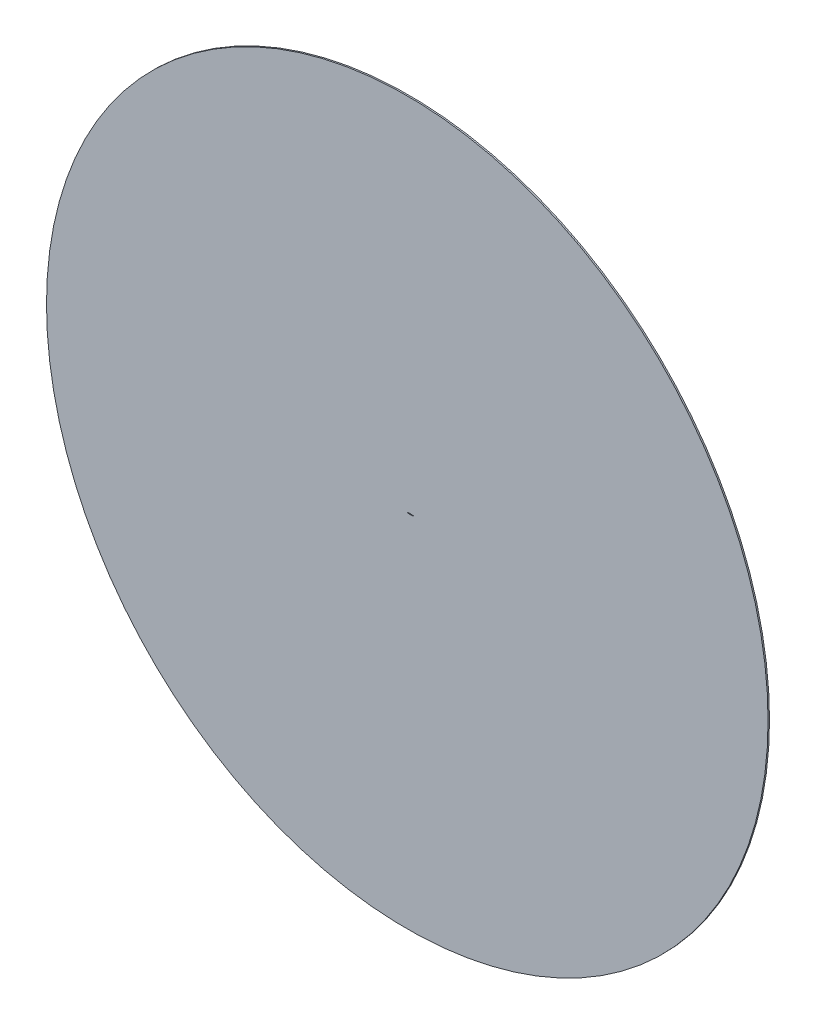
SolidWorks part; units mm, degrees
ref_plane "Front Plane" through (0, 0, 0) normal (0, 0, 1) x (1, 0, 0)
ref_plane "Top Plane" through (0, 0, 0) normal (0, 1, 0) x (1, 0, 0)
ref_plane "Right Plane" through (0, 0, 0) normal (1, 0, 0) x (0, 0, -1)
curve "Curve1"
  spline degree 3 poles (609.0266, -0.065, 0) (609.7435, 0, 0) (609.0266, 0.065, 0) (608.4348, 0.1812, 0) (606.982, 0.3745, 0) (605.1708, 0.6429, 0) (602.7599, 0.9868, 0) (599.8538, 1.4027, 0) (596.4201, 1.8894, 0) (592.4782, 2.4453, 0) (588.0305, 3.0658, 0) (583.0864, 3.7497, 0) (577.6538, 4.4919, 0) (571.7427, 5.2915, 0) (565.3633, 6.1431, 0) (558.5267, 7.0435, 0) (551.2452, 7.989, 0) (543.5311, 8.9751, 0) (535.3983, 9.9995, 0) (526.861, 11.0564, 0) (517.9338, 12.1418, 0) (508.6331, 13.2534, 0) (498.9745, 14.3843, 0) (488.9755, 15.5329, 0) (478.6533, 16.6942, 0) (468.0259, 17.8633, 0) (457.1122, 19.0358, 0) (445.9317, 20.2096, 0) (434.5033, 21.3779, 0) (422.8474, 22.5382, 0) (410.9843, 23.685, 0) (398.9349, 24.8131, 0) (386.7204, 25.9202, 0) (374.3624, 26.9991, 0) (361.8823, 28.0468, 0) (349.3021, 29.058, 0) (336.6435, 30.027, 0) (323.9291, 30.9493, 0) (311.1813, 31.8197, 0) (298.4224, 32.6341, 0) (285.6746, 33.3849, 0) (272.9601, 34.0701, 0) (260.3015, 34.6833, 0) (247.721, 35.219, 0) (235.2407, 35.6733, 0) (222.8825, 36.0416, 0) (210.6677, 36.3202, 0) (198.618, 36.5039, 0) (186.7544, 36.5908, 0) (175.098, 36.576, 0) (163.669, 36.4591, 0) (152.4878, 36.2354, 0) (141.5734, 35.9063, 0) (130.9453, 35.4671, 0) (120.622, 34.9205, 0) (110.622, 34.2646, 0) (100.9624, 33.5002, 0) (91.6602, 32.63, 0) (82.7316, 31.6541, 0) (74.1925, 30.5757, 0) (66.0576, 29.3979, 0) (58.3413, 28.1224, 0) (51.0569, 26.7548, 0) (44.2171, 25.2975, 0) (37.8335, 23.7562, 0) (31.9176, 22.1329, 0) (26.4786, 20.4359, 0) (21.5267, 18.6662, 0) (17.0689, 16.8301, 0) (13.1127, 14.9307, 0) (9.6631, 12.973, 0) (6.7256, 10.9577, 0) (4.3029, 8.8862, 0) (2.3998, 6.7558, 0) (1.0219, 4.5626, 0) (0.1859, 2.3028, 0) (-0.0912, 0, 0) (0.1859, -2.3028, 0) (1.0219, -4.5626, 0) (2.3998, -6.7558, 0) (4.3029, -8.8862, 0) (6.7256, -10.9577, 0) (9.6631, -12.973, 0) (13.1127, -14.9307, 0) (17.0689, -16.8301, 0) (21.5267, -18.6662, 0) (26.4786, -20.4359, 0) (31.9176, -22.1329, 0) (37.8335, -23.7562, 0) (44.2171, -25.2975, 0) (51.0569, -26.7548, 0) (58.3413, -28.1224, 0) (66.0576, -29.3979, 0) (74.1925, -30.5757, 0) (82.7316, -31.6541, 0) (91.6602, -32.63, 0) (100.9624, -33.5002, 0) (110.622, -34.2646, 0) (120.622, -34.9205, 0) (130.9453, -35.4671, 0) (141.5734, -35.9063, 0) (152.4878, -36.2354, 0) (163.669, -36.4591, 0) (175.098, -36.576, 0) (186.7544, -36.5908, 0) (198.618, -36.5039, 0) (210.6677, -36.3202, 0) (222.8825, -36.0416, 0) (235.2407, -35.6733, 0) (247.721, -35.219, 0) (260.3015, -34.6833, 0) (272.9601, -34.0701, 0) (285.6746, -33.3849, 0) (298.4224, -32.6341, 0) (311.1813, -31.8197, 0) (323.9291, -30.9493, 0) (336.6435, -30.027, 0) (349.3021, -29.058, 0) (361.8823, -28.0468, 0) (374.3624, -26.9991, 0) (386.7204, -25.9202, 0) (398.9349, -24.8131, 0) (410.9843, -23.685, 0) (422.8474, -22.5382, 0) (434.5033, -21.3779, 0) (445.9317, -20.2096, 0) (457.1122, -19.0358, 0) (468.0259, -17.8633, 0) (478.6533, -16.6942, 0) (488.9755, -15.5329, 0) (498.9745, -14.3843, 0) (508.6331, -13.2534, 0) (517.9338, -12.1418, 0) (526.861, -11.0564, 0) (535.3983, -9.9995, 0) (543.5311, -8.9751, 0) (551.2452, -7.989, 0) (558.5267, -7.0435, 0) (565.3633, -6.1431, 0) (571.7427, -5.2915, 0) (577.6538, -4.4919, 0) (583.0864, -3.7497, 0) (588.0305, -3.0658, 0) (592.4782, -2.4453, 0) (596.4201, -1.8894, 0) (599.8538, -1.4027, 0) (602.7599, -0.9868, 0) (605.1708, -0.6429, 0) (606.982, -0.3745, 0) (608.4348, -0.1812, 0) (609.0266, -0.065, 0) (609.7435, 0, 0) (609.0266, 0.065, 0) knots -0.001954 -0.000869 -0.000218 0 0.000218 0.000869 0.001954 0.003469 0.005413 0.007781 0.01057 0.013775 0.017389 0.021406 0.025819 0.03062 0.0358 0.041349 0.047259 0.053518 0.060115 0.067039 0.074276 0.081815 0.089641 0.097741 0.106101 0.114706 0.12354 0.132588 0.141833 0.15126 0.160852 0.170592 0.180463 0.190447 0.200526 0.210683 0.220901 0.23116 0.241444 0.251733 0.26201 0.272258 0.282457 0.292591 0.302642 0.312592 0.322425 0.332124 0.341671 0.351052 0.36025 0.369251 0.378038 0.386598 0.394918 0.402982 0.41078 0.418299 0.425526 0.432452 0.439066 0.445359 0.451323 0.456949 0.462232 0.467167 0.471749 0.475977 0.479852 0.483377 0.48656 0.489414 0.491961 0.494234 0.496281 0.498175 0.5 0.501825 0.503719 0.505766 0.508039 0.510586 0.51344 0.516623 0.520148 0.524023 0.528251 0.532833 0.537768 0.543051 0.548677 0.554641 0.560934 0.567548 0.574474 0.581701 0.58922 0.597018 0.605082 0.613402 0.621962 0.630749 0.63975 0.648948 0.658329 0.667876 0.677575 0.687408 0.697358 0.707409 0.717543 0.727742 0.73799 0.748267 0.758556 0.76884 0.779099 0.789317 0.799474 0.809553 0.819537 0.829408 0.839148 0.84874 0.858167 0.867412 0.87646 0.885294 0.893899 0.902259 0.910359 0.918185 0.925724 0.932961 0.939885 0.946482 0.952741 0.958651 0.9642 0.96938 0.974181 0.978594 0.982611 0.986225 0.98943 0.992219 0.994587 0.996531 0.998046 0.999131 0.999782 1 1.000218 1.000869 1.001954 periodic
sketch "Sketch1" plane through (0, 0, 0) normal (0, 0, 1) x (1, 0, 0)
  circle A0 centre (0, 0) radius 30480
  spline S0 degree 3 poles (609.0266, -0.065) (609.7435, 0) (609.0266, 0.065) (608.4348, 0.1812) (606.982, 0.3745) (605.1708, 0.6429) (602.7599, 0.9868) (599.8538, 1.4027) (596.4201, 1.8894) (592.4782, 2.4453) (588.0305, 3.0658) (583.0864, 3.7497) (577.6538, 4.4919) (571.7427, 5.2915) (565.3633, 6.1431) (558.5267, 7.0435) (551.2452, 7.989) (543.5311, 8.9751) (535.3983, 9.9995) (526.861, 11.0564) (517.9338, 12.1418) (508.6331, 13.2534) (498.9745, 14.3843) (488.9755, 15.5329) (478.6533, 16.6942) (468.0259, 17.8633) (457.1122, 19.0358) (445.9317, 20.2096) (434.5033, 21.3779) (422.8474, 22.5382) (410.9843, 23.685) (398.9349, 24.8131) (386.7204, 25.9202) (374.3624, 26.9991) (361.8823, 28.0468) (349.3021, 29.058) (336.6435, 30.027) (323.9291, 30.9493) (311.1813, 31.8197) (298.4224, 32.6341) (285.6746, 33.3849) (272.9601, 34.0701) (260.3015, 34.6833) (247.721, 35.219) (235.2407, 35.6733) (222.8825, 36.0416) (210.6677, 36.3202) (198.618, 36.5039) (186.7544, 36.5908) (175.098, 36.576) (163.669, 36.4591) (152.4878, 36.2354) (141.5734, 35.9063) (130.9453, 35.4671) (120.622, 34.9205) (110.622, 34.2646) (100.9624, 33.5002) (91.6602, 32.63) (82.7316, 31.6541) (74.1925, 30.5757) (66.0576, 29.3979) (58.3413, 28.1224) (51.0569, 26.7548) (44.2171, 25.2975) (37.8335, 23.7562) (31.9176, 22.1329) (26.4786, 20.4359) (21.5267, 18.6662) (17.0689, 16.8301) (13.1127, 14.9307) (9.6631, 12.973) (6.7256, 10.9577) (4.3029, 8.8862) (2.3998, 6.7558) (1.0219, 4.5626) (0.1859, 2.3028) (-0.0912, 0) (0.1859, -2.3028) (1.0219, -4.5626) (2.3998, -6.7558) (4.3029, -8.8862) (6.7256, -10.9577) (9.6631, -12.973) (13.1127, -14.9307) (17.0689, -16.8301) (21.5267, -18.6662) (26.4786, -20.4359) (31.9176, -22.1329) (37.8335, -23.7562) (44.2171, -25.2975) (51.0569, -26.7548) (58.3413, -28.1224) (66.0576, -29.3979) (74.1925, -30.5757) (82.7316, -31.6541) (91.6602, -32.63) (100.9624, -33.5002) (110.622, -34.2646) (120.622, -34.9205) (130.9453, -35.4671) (141.5734, -35.9063) (152.4878, -36.2354) (163.669, -36.4591) (175.098, -36.576) (186.7544, -36.5908) (198.618, -36.5039) (210.6677, -36.3202) (222.8825, -36.0416) (235.2407, -35.6733) (247.721, -35.219) (260.3015, -34.6833) (272.9601, -34.0701) (285.6746, -33.3849) (298.4224, -32.6341) (311.1813, -31.8197) (323.9291, -30.9493) (336.6435, -30.027) (349.3021, -29.058) (361.8823, -28.0468) (374.3624, -26.9991) (386.7204, -25.9202) (398.9349, -24.8131) (410.9843, -23.685) (422.8474, -22.5382) (434.5033, -21.3779) (445.9317, -20.2096) (457.1122, -19.0358) (468.0259, -17.8633) (478.6533, -16.6942) (488.9755, -15.5329) (498.9745, -14.3843) (508.6331, -13.2534) (517.9338, -12.1418) (526.861, -11.0564) (535.3983, -9.9995) (543.5311, -8.9751) (551.2452, -7.989) (558.5267, -7.0435) (565.3633, -6.1431) (571.7427, -5.2915) (577.6538, -4.4919) (583.0864, -3.7497) (588.0305, -3.0658) (592.4782, -2.4453) (596.4201, -1.8894) (599.8538, -1.4027) (602.7599, -0.9868) (605.1708, -0.6429) (606.982, -0.3745) (608.4348, -0.1812) (609.0266, -0.065) (609.7435, 0) (609.0266, 0.065) knots -0.001954 -0.000869 -0.000218 0 0.000218 0.000869 0.001954 0.003469 0.005413 0.007781 0.01057 0.013775 0.017389 0.021406 0.025819 0.03062 0.0358 0.041349 0.047259 0.053518 0.060115 0.067039 0.074276 0.081815 0.089641 0.097741 0.106101 0.114706 0.12354 0.132588 0.141833 0.15126 0.160852 0.170592 0.180463 0.190447 0.200526 0.210683 0.220901 0.23116 0.241444 0.251733 0.26201 0.272258 0.282457 0.292591 0.302642 0.312592 0.322425 0.332124 0.341671 0.351052 0.36025 0.369251 0.378038 0.386598 0.394918 0.402982 0.41078 0.418299 0.425526 0.432452 0.439066 0.445359 0.451323 0.456949 0.462232 0.467167 0.471749 0.475977 0.479852 0.483377 0.48656 0.489414 0.491961 0.494234 0.496281 0.498175 0.5 0.501825 0.503719 0.505766 0.508039 0.510586 0.51344 0.516623 0.520148 0.524023 0.528251 0.532833 0.537768 0.543051 0.548677 0.554641 0.560934 0.567548 0.574474 0.581701 0.58922 0.597018 0.605082 0.613402 0.621962 0.630749 0.63975 0.648948 0.658329 0.667876 0.677575 0.687408 0.697358 0.707409 0.717543 0.727742 0.73799 0.748267 0.758556 0.76884 0.779099 0.789317 0.799474 0.809553 0.819537 0.829408 0.839148 0.84874 0.858167 0.867412 0.87646 0.885294 0.893899 0.902259 0.910359 0.918185 0.925724 0.932961 0.939885 0.946482 0.952741 0.958651 0.9642 0.96938 0.974181 0.978594 0.982611 0.986225 0.98943 0.992219 0.994587 0.996531 0.998046 0.999131 0.999782 1 1.000218 1.000869 1.001954 only from (609.6, 0) to (609.6, 0) construction
  spline S1 degree 3 poles (609.0266, -0.065) (609.7435, 0) (609.0266, 0.065) (608.4348, 0.1812) (606.982, 0.3745) (605.1708, 0.6429) (602.7599, 0.9868) (599.8538, 1.4027) (596.4201, 1.8894) (592.4782, 2.4453) (588.0305, 3.0658) (583.0864, 3.7497) (577.6538, 4.4919) (571.7427, 5.2915) (565.3633, 6.1431) (558.5267, 7.0435) (551.2452, 7.989) (543.5311, 8.9751) (535.3983, 9.9995) (526.861, 11.0564) (517.9338, 12.1418) (508.6331, 13.2534) (498.9745, 14.3843) (488.9755, 15.5329) (478.6533, 16.6942) (468.0259, 17.8633) (457.1122, 19.0358) (445.9317, 20.2096) (434.5033, 21.3779) (422.8474, 22.5382) (410.9843, 23.685) (398.9349, 24.8131) (386.7204, 25.9202) (374.3624, 26.9991) (361.8823, 28.0468) (349.3021, 29.058) (336.6435, 30.027) (323.9291, 30.9493) (311.1813, 31.8197) (298.4224, 32.6341) (285.6746, 33.3849) (272.9601, 34.0701) (260.3015, 34.6833) (247.721, 35.219) (235.2407, 35.6733) (222.8825, 36.0416) (210.6677, 36.3202) (198.618, 36.5039) (186.7544, 36.5908) (175.098, 36.576) (163.669, 36.4591) (152.4878, 36.2354) (141.5734, 35.9063) (130.9453, 35.4671) (120.622, 34.9205) (110.622, 34.2646) (100.9624, 33.5002) (91.6602, 32.63) (82.7316, 31.6541) (74.1925, 30.5757) (66.0576, 29.3979) (58.3413, 28.1224) (51.0569, 26.7548) (44.2171, 25.2975) (37.8335, 23.7562) (31.9176, 22.1329) (26.4786, 20.4359) (21.5267, 18.6662) (17.0689, 16.8301) (13.1127, 14.9307) (9.6631, 12.973) (6.7256, 10.9577) (4.3029, 8.8862) (2.3998, 6.7558) (1.0219, 4.5626) (0.1859, 2.3028) (-0.0912, 0) (0.1859, -2.3028) (1.0219, -4.5626) (2.3998, -6.7558) (4.3029, -8.8862) (6.7256, -10.9577) (9.6631, -12.973) (13.1127, -14.9307) (17.0689, -16.8301) (21.5267, -18.6662) (26.4786, -20.4359) (31.9176, -22.1329) (37.8335, -23.7562) (44.2171, -25.2975) (51.0569, -26.7548) (58.3413, -28.1224) (66.0576, -29.3979) (74.1925, -30.5757) (82.7316, -31.6541) (91.6602, -32.63) (100.9624, -33.5002) (110.622, -34.2646) (120.622, -34.9205) (130.9453, -35.4671) (141.5734, -35.9063) (152.4878, -36.2354) (163.669, -36.4591) (175.098, -36.576) (186.7544, -36.5908) (198.618, -36.5039) (210.6677, -36.3202) (222.8825, -36.0416) (235.2407, -35.6733) (247.721, -35.219) (260.3015, -34.6833) (272.9601, -34.0701) (285.6746, -33.3849) (298.4224, -32.6341) (311.1813, -31.8197) (323.9291, -30.9493) (336.6435, -30.027) (349.3021, -29.058) (361.8823, -28.0468) (374.3624, -26.9991) (386.7204, -25.9202) (398.9349, -24.8131) (410.9843, -23.685) (422.8474, -22.5382) (434.5033, -21.3779) (445.9317, -20.2096) (457.1122, -19.0358) (468.0259, -17.8633) (478.6533, -16.6942) (488.9755, -15.5329) (498.9745, -14.3843) (508.6331, -13.2534) (517.9338, -12.1418) (526.861, -11.0564) (535.3983, -9.9995) (543.5311, -8.9751) (551.2452, -7.989) (558.5267, -7.0435) (565.3633, -6.1431) (571.7427, -5.2915) (577.6538, -4.4919) (583.0864, -3.7497) (588.0305, -3.0658) (592.4782, -2.4453) (596.4201, -1.8894) (599.8538, -1.4027) (602.7599, -0.9868) (605.1708, -0.6429) (606.982, -0.3745) (608.4348, -0.1812) (609.0266, -0.065) (609.7435, 0) (609.0266, 0.065) knots -0.001954 -0.000869 -0.000218 0 0.000218 0.000869 0.001954 0.003469 0.005413 0.007781 0.01057 0.013775 0.017389 0.021406 0.025819 0.03062 0.0358 0.041349 0.047259 0.053518 0.060115 0.067039 0.074276 0.081815 0.089641 0.097741 0.106101 0.114706 0.12354 0.132588 0.141833 0.15126 0.160852 0.170592 0.180463 0.190447 0.200526 0.210683 0.220901 0.23116 0.241444 0.251733 0.26201 0.272258 0.282457 0.292591 0.302642 0.312592 0.322425 0.332124 0.341671 0.351052 0.36025 0.369251 0.378038 0.386598 0.394918 0.402982 0.41078 0.418299 0.425526 0.432452 0.439066 0.445359 0.451323 0.456949 0.462232 0.467167 0.471749 0.475977 0.479852 0.483377 0.48656 0.489414 0.491961 0.494234 0.496281 0.498175 0.5 0.501825 0.503719 0.505766 0.508039 0.510586 0.51344 0.516623 0.520148 0.524023 0.528251 0.532833 0.537768 0.543051 0.548677 0.554641 0.560934 0.567548 0.574474 0.581701 0.58922 0.597018 0.605082 0.613402 0.621962 0.630749 0.63975 0.648948 0.658329 0.667876 0.677575 0.687408 0.697358 0.707409 0.717543 0.727742 0.73799 0.748267 0.758556 0.76884 0.779099 0.789317 0.799474 0.809553 0.819537 0.829408 0.839148 0.84874 0.858167 0.867412 0.87646 0.885294 0.893899 0.902259 0.910359 0.918185 0.925724 0.932961 0.939885 0.946482 0.952741 0.958651 0.9642 0.96938 0.974181 0.978594 0.982611 0.986225 0.98943 0.992219 0.994587 0.996531 0.998046 0.999131 0.999782 1 1.000218 1.000869 1.001954 only from (609.6, 0) to (609.6, 0)
  dimension "D1" = 60960
extrude "Boss-Extrude1" add sketch "Sketch1" along normal blind 121.92
